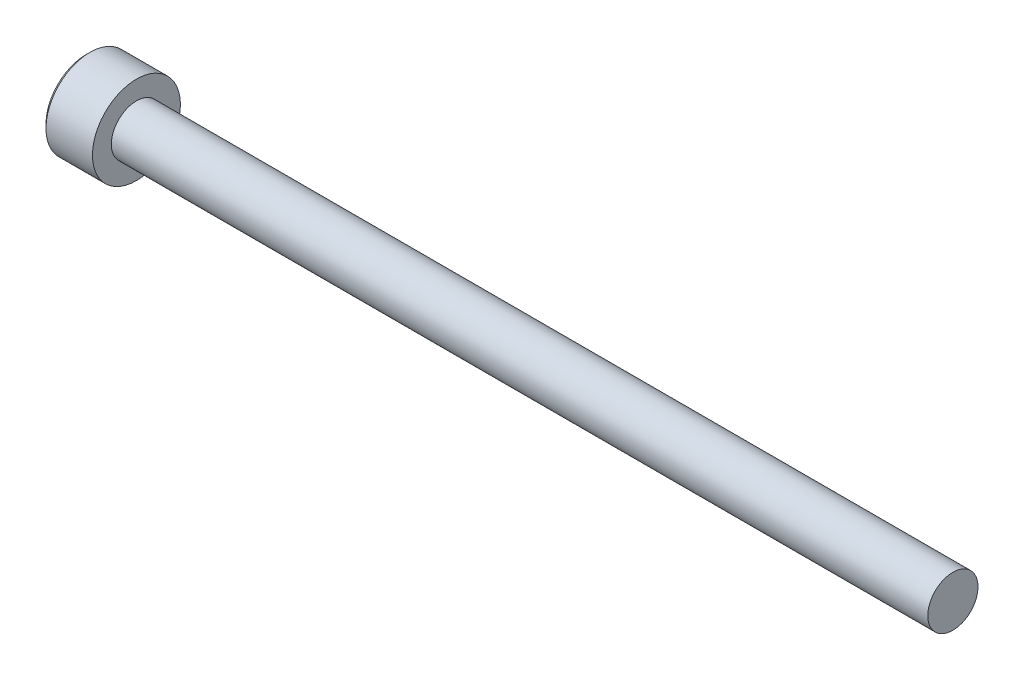
SolidWorks part; units mm, degrees
ref_plane "Front Plane" through (0, 0, 0) normal (0, 0, 1) x (1, 0, 0)
ref_plane "Top Plane" through (0, 0, 0) normal (0, 1, 0) x (1, 0, 0)
ref_plane "Right Plane" through (0, 0, 0) normal (1, 0, 0) x (0, 0, -1)
sketch "Sketch1" plane through (0, 0, 0) normal (0, 0, 1) x (1, 0, 0)
  line L0 (-4, 0) -> (65, 0) construction
  line L1 (-4, 0) -> (-4, 3.2)
  line L2 (-3.7, 3.5) -> (0, 3.5)
  line L3 (0, 3.5) -> (0, 2)
  line L4 (0, 2) -> (65, 2)
  line L5 (65, 2) -> (65, 0)
  line L6 (65, 0) -> (-4, 0)
  line L7 (-4, 3.2) -> (-3.7, 3.5)
  point P4 (-4, 3.5)
  dimension "FIX_4" = 7
  dimension "FIX_5" = 4
  dimension "FIX_1" = 4
  dimension "FIX_2" = 65
revolve "Revolve1" add sketch "Sketch1" about L0
cosmetic thread "Thread201" parameters "NFIX_1"=3.242
sketch "Sketch2" plane through (-4, 0, 0) normal (-1, 0, 0) x (0, 0, 1)
  line L1 (0, 1.7321) -> (-1.5, 0.866)
  line L2 (-1.5, 0.866) -> (-1.5, -0.866)
  line L3 (-1.5, -0.866) -> (0, -1.7321)
  line L4 (0, -1.7321) -> (1.5, -0.866)
  line L5 (1.5, -0.866) -> (1.5, 0.866)
  line L6 (1.5, 0.866) -> (0, 1.7321)
  circle A0 centre (0, 0) radius 1.5 construction
extrude "Cut-Extrude1" cut sketch "Sketch2" against normal blind 2
sketch "Sketch3" plane through (0, 0, 0) normal (0, 0, 1) x (1, 0, 0)
  line L0 (-2, 0) -> (-1.0987, 0) construction
  line L1 (-2, 0) -> (-2, 1.5)
  line L2 (-2, 1.5) -> (-1.0987, 0)
  line L3 (-1.0987, 0) -> (-2, 0)
  line L4 (-2, 0.866) -> (-2, -0.866) construction
  dimension "FIX_9" = 59
revolve "Cut-Revolve1" cut sketch "Sketch3" about L0
